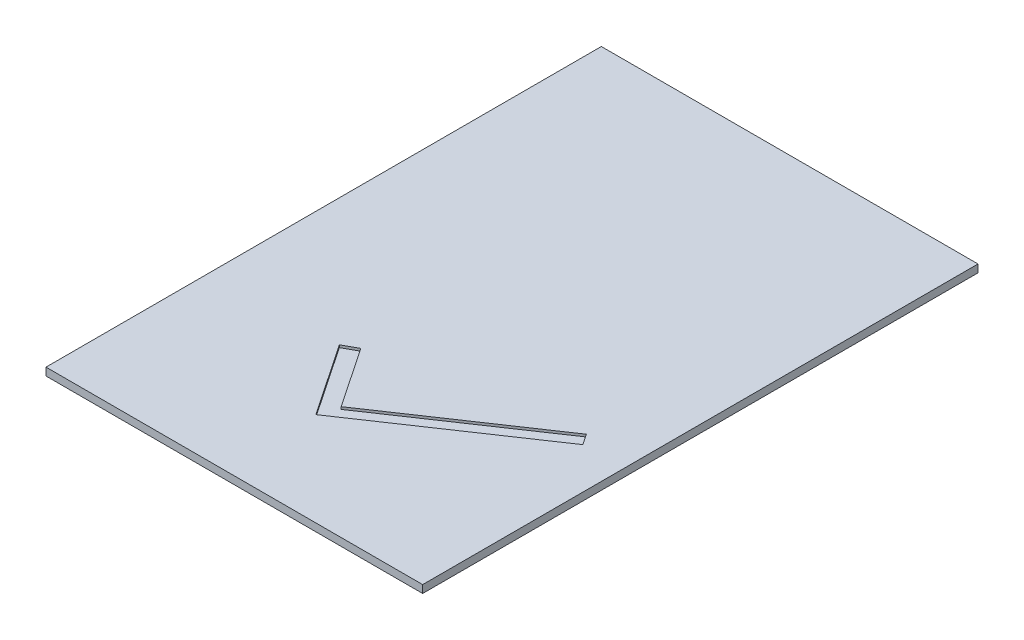
SolidWorks part; units mm, degrees
ref_plane "Front Plane" through (0, 0, 0) normal (0, 0, 1) x (1, 0, 0)
ref_plane "Top Plane" through (0, 0, 0) normal (0, 1, 0) x (1, 0, 0)
ref_plane "Right Plane" through (0, 0, 0) normal (1, 0, 0) x (0, 0, -1)
sketch "Sketch1" plane through (0, 0, 0) normal (0, 1, 0) x (1, 0, 0)
  line L1 (0, 0) -> (78, 0)
  line L2 (0, 0) -> (0, 115)
  line L3 (0, 115) -> (78, 115)
  line L4 (78, 0) -> (78, 115)
  dimension "D1" = 115
  dimension "D2" = 78
extrude "Boss-Extrude1" add sketch "Sketch1" along normal blind 1.6
sketch "Sketch2" plane through (0, 1.6, 0) normal (0, 1, 0) x (1, 0, 0)
  line L0 (29.2391, 35.9546) -> (37.6483, 23.4765)
  line L1 (37.6483, 23.4765) -> (67.9857, 43.9214)
  line L2 (67.9857, 43.9214) -> (69.4944, 41.6827)
  line L3 (69.4944, 41.6827) -> (36.4556, 19.4174)
  line L4 (36.4556, 19.4174) -> (26.3795, 34.3691)
  line L5 (26.3795, 34.3691) -> (29.2391, 35.9546)
extrude "Cut-Extrude1" cut sketch "Sketch2" against normal blind 0.5
